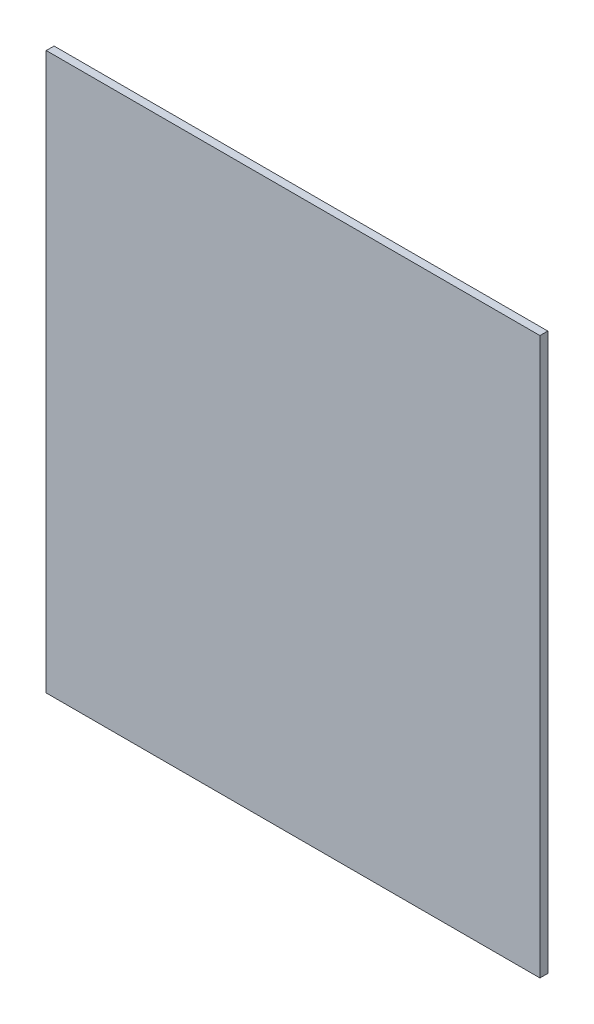
SolidWorks part; units mm, degrees
ref_plane "Front Plane" through (0, 0, 0) normal (0, 0, 1) x (1, 0, 0)
ref_plane "Top Plane" through (0, 0, 0) normal (0, 1, 0) x (1, 0, 0)
ref_plane "Right Plane" through (0, 0, 0) normal (1, 0, 0) x (0, 0, -1)
sketch "Sketch1" plane through (0, 0, 0) normal (0, 0, 1) x (1, 0, 0)
  line L1 (-200.025, 225.425) -> (200.025, 225.425)
  line L2 (-200.025, 225.425) -> (-200.025, -225.425)
  line L3 (-200.025, -225.425) -> (200.025, -225.425)
  line L4 (200.025, 225.425) -> (200.025, -225.425)
  point P4 (265.5841, -181.8916)
  point P5 (0, -225.425)
  point P7 (-200.025, 0)
  dimension "D1" = 400.05
  dimension "D2" = 450.85
extrude "Boss-Extrude1" add sketch "Sketch1" along normal blind 6.35
